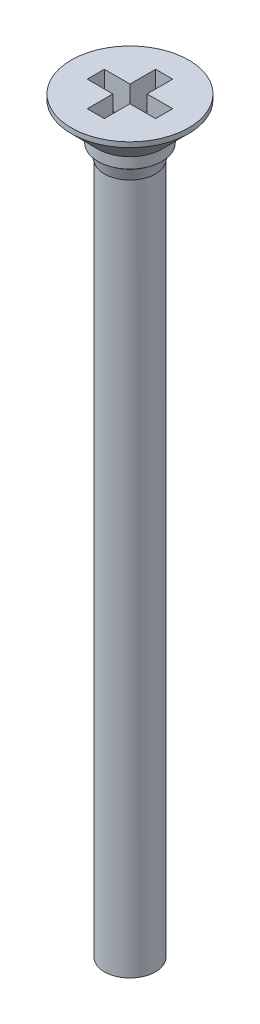
SolidWorks part; units mm, degrees
ref_plane "Vorderseite" through (0, 0, 0) normal (0, 0, 1) x (1, 0, 0)
ref_plane "Oben" through (0, 0, 0) normal (0, 1, 0) x (1, 0, 0)
ref_plane "Rechts" through (0, 0, 0) normal (1, 0, 0) x (0, 0, -1)
sketch "Skizze1" plane through (0, 0, 0) normal (0, 0, 1) x (1, 0, 0)
  line L0 (0, 0) -> (2.75, 0)
  line L1 (2.75, 0) -> (2.75, -0.2375)
  line L2 (2.75, -0.2375) -> (1.5, -1.4875)
  line L3 (1.3375, -1.9875) -> (1.3375, -2.1126)
  line L4 (1.3375, -2.1126) -> (1.1935, -2.65)
  line L5 (1.1935, -2.65) -> (1.1935, -8)
  line L6 (1.1935, -8) -> (0, -8)
  line L7 (0, 0) -> (0, -8) construction
  line L8 (0, 0) -> (0, -8)
  line L10 (1.5, -1.4875) -> (1.5, -1.9875)
  line L12 (1.5, -1.9875) -> (1.3375, -1.9875)
  point P3 (1.3375, -1.65)
  dimension "D1" = 45
  dimension "D2" = 15
  dimension "K" = 1.65
  dimension "DA" = 5.5
  dimension "DK" = 2.387
  dimension "L" = 8
  dimension "DG" = 3
  dimension "A" = 1
  dimension "DF" = 2.675
  dimension "P" = 0.5
revolve "Basis-Rotation" add sketch "Skizze1" angle 360 about L7
sketch "Skizze2" plane through (0, 0, 0) normal (0, 0, 1) x (1, 0, 0)
  line L0 (0, -2.1) -> (0, 0) construction
  line L1 (0, 0) -> (0, -8) construction
  line L2 (-0.55, -2.1) -> (0.55, -2.1)
  line L3 (1.6, 0) -> (1.6, -1.05)
  line L4 (1.6, -1.05) -> (0.55, -2.1)
  line L5 (1.6, 0) -> (-1.6, 0)
  line L6 (-1.6, -1.05) -> (-0.55, -2.1)
  line L7 (-1.6, 0) -> (-1.6, -1.05)
  line L8 (0, -1.05) -> (1.6, -1.05) construction
  line L9 (2.75, 0) -> (-2.75, 0) construction
  line L11 (1.5, -1.4875) -> (2.75, -0.2375) construction
  point P11 (0, 0)
  dimension "M" = 3.2
  dimension "T" = 2.1
extrude "Kreuzschlitz1 H" cut sketch "Skizze2" against normal blind 0.4 and the other way blind 0.4
sketch "Skizze3" plane through (0, 0, 0) normal (1, 0, 0) x (0, 0, -1)
  line L0 (0, -2.1) -> (0, 0) construction
  line L2 (-0.55, -2.1) -> (0.55, -2.1)
  line L3 (1.6, 0) -> (1.6, -1.05)
  line L4 (1.6, -1.05) -> (0.55, -2.1)
  line L5 (1.6, 0) -> (-1.6, 0)
  line L6 (-1.6, -1.05) -> (-0.55, -2.1)
  line L7 (-1.6, 0) -> (-1.6, -1.05)
  line L8 (0, -1.05) -> (1.6, -1.05) construction
  point P11 (0, 0)
extrude "Kreuzschlitz2 H" cut sketch "Skizze3" against normal blind 0.4 and the other way blind 0.4
sketch "Skizze4" plane through (2.4522, 0, -1.8507) normal (0, 1, 0) x (-1, 0, 0)
  line L0 (7.3522, 1.8507) -> (-2.4478, 1.8507) construction
  line L1 (2.4522, -3.0493) -> (2.4522, 6.7507) construction
  line L2 (-2.4478, 1.0342) -> (-2.4478, 2.6672)
  line L3 (-2.4478, 1.0342) -> (0.0059, 1.0342)
  line L4 (0.0059, 1.0342) -> (0.8191, 0.6258)
  line L5 (1.2273, 0.2176) -> (-1.0126, -1.6141)
  line L6 (0.8191, 0.6258) -> (-1.0126, -1.6141)
  line L7 (1.6357, -0.5956) -> (1.2273, 0.2176)
  line L8 (1.6357, -3.0493) -> (1.6357, -0.5956)
  line L9 (1.6357, -3.0493) -> (3.2687, -3.0493)
  line L10 (3.2687, -3.0493) -> (3.2687, -0.5956)
  line L11 (3.2687, -0.5956) -> (3.6772, 0.2176)
  line L12 (2.4522, 1.8507) -> (-1.0126, -1.6141) construction
  line L13 (4.0854, 0.6258) -> (5.917, -1.6141)
  line L14 (3.6772, 0.2176) -> (5.917, -1.6141)
  line L15 (4.8986, 1.0342) -> (4.0854, 0.6258)
  line L16 (7.3522, 1.0342) -> (4.8986, 1.0342)
  line L17 (7.3522, 1.0342) -> (7.3522, 2.6672)
  line L18 (7.3522, 2.6672) -> (4.8986, 2.6672)
  line L19 (4.8986, 2.6672) -> (4.0854, 3.0757)
  line L20 (3.6772, 3.4839) -> (5.917, 5.3156)
  line L21 (4.0854, 3.0757) -> (5.917, 5.3156)
  line L22 (3.2687, 4.2971) -> (3.6772, 3.4839)
  line L23 (3.2687, 6.7507) -> (3.2687, 4.2971)
  line L24 (1.6357, 6.7507) -> (3.2687, 6.7507)
  line L25 (1.6357, 6.7507) -> (1.6357, 4.2971)
  line L26 (1.6357, 4.2971) -> (1.2273, 3.4839)
  line L27 (0.8191, 3.0757) -> (-1.0126, 5.3156)
  line L28 (1.2273, 3.4839) -> (-1.0126, 5.3156)
  line L29 (0.0059, 2.6672) -> (0.8191, 3.0757)
  line L30 (-2.4478, 2.6672) -> (0.0059, 2.6672)
  circle A0 centre (2.4522, 1.8507) radius 4.9 construction
  circle A1 centre (2.4522, 1.8507) radius 2.0415 construction
  circle A2 centre (2.4522, 1.8507) radius 2.579 construction
  dimension "X2" = 4.083
  dimension "X1" = 5.158
  dimension "M" = 9.8
  dimension "D3" = 5.725
  dimension "X3" = 1.633
sketch "Sketch1" plane through (0, -8, 0) normal (0, -1, 0) x (1, 0, 0)
  circle A0 centre (0, 0) radius 1.1935
extrude "Boss-Extrude1" add sketch "Sketch1" along normal blind 27
